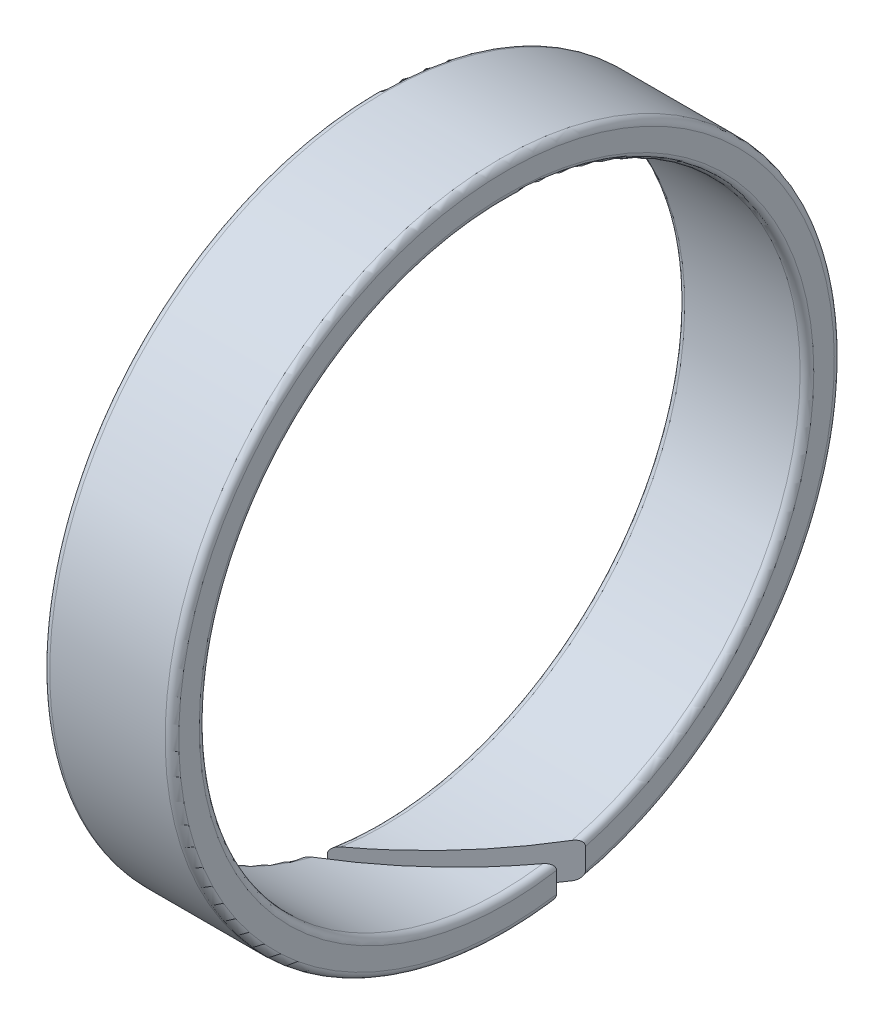
SolidWorks part; units mm, degrees
ref_plane "Front Plane" through (0, 0, 0) normal (0, 0, 1) x (1, 0, 0)
ref_plane "Top Plane" through (0, 0, 0) normal (0, 1, 0) x (1, 0, 0)
ref_plane "Right Plane" through (0, 0, 0) normal (1, 0, 0) x (0, 0, -1)
sketch "Sketch1" plane through (0, 0, 0) normal (1, 0, 0) x (0, 0, -1)
  circle A0 centre (0, 0) radius 24.5
  circle A1 centre (0, 0) radius 22
  dimension "D1" = 49
  dimension "D2" = 2.5
extrude "Extrude1" add sketch "Sketch1" along normal mid plane 9.45
sketch "Sketch2" plane through (0, 0, 0) normal (0, 1, 0) x (1, 0, 0)
  line L0 (0, 0) -> (7.9859, 7.9859) construction
  line L1 (0, 0) -> (8.4936, 0) construction
  line L2 (4.725, 5.7857) -> (-5.7206, -4.66)
  line L3 (5.7857, 4.725) -> (-4.66, -5.7206)
  line L4 (4.725, 5.7857) -> (5.7857, 4.725)
  line L5 (-5.7206, -4.66) -> (-4.66, -5.7206)
  line L7 (4.725, -24.5) -> (4.725, 24.5) construction
  dimension "D1" = 45
  dimension "D2" = 1.5
extrude "Extrude2" cut sketch "Sketch2" against normal through all
fillet "Fillet1" radius 0.5 4 edges at (-4.725, 24.052, -4.664) (-4.725, 21.4997, -4.665) (4.725, 21.4853, 4.7308) (4.725, 24.0392, 4.7296)
